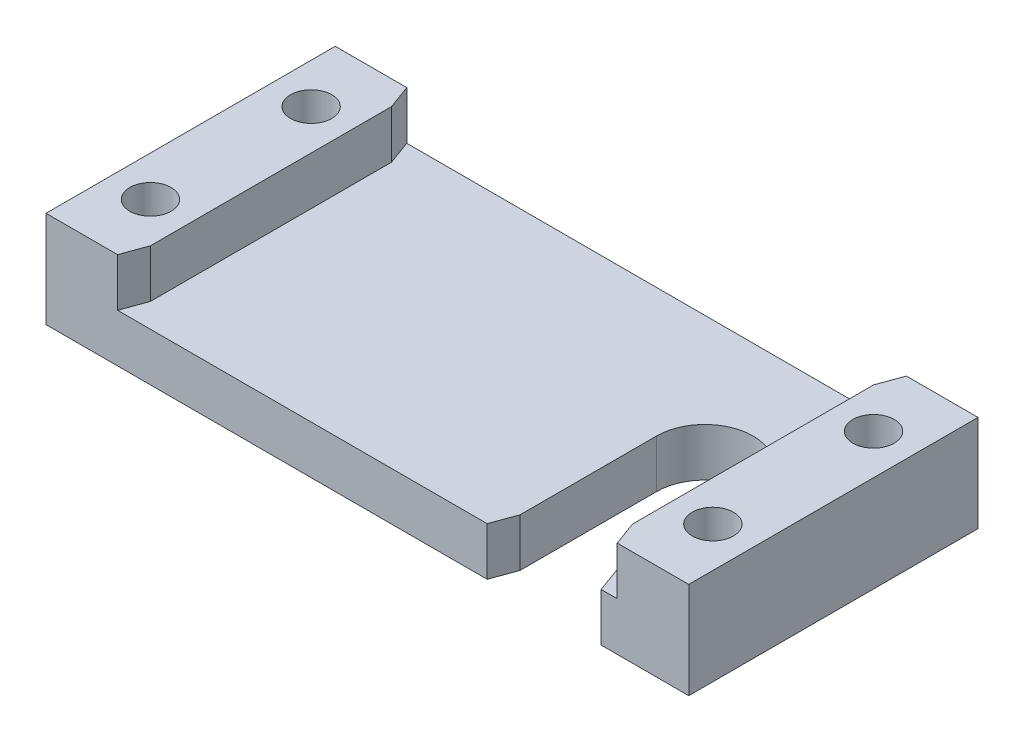
SolidWorks part; units mm, degrees
material "Delrin 2700 NC010, Low Viscosity Acetal Copolymer (SS)"
ref_plane "Front Plane" through (0, 0, 0) normal (0, 0, 1) x (1, 0, 0)
ref_plane "Top Plane" through (0, 0, 0) normal (0, 1, 0) x (1, 0, 0)
ref_plane "Right Plane" through (0, 0, 0) normal (1, 0, 0) x (0, 0, -1)
sketch "Sketch1" plane through (0, 0, 0) normal (0, 0, 1) x (1, 0, 0)
  line L1 (-25.4, 3.81) -> (25.4, 3.81)
  line L2 (-25.4, 3.81) -> (-25.4, -3.81)
  line L3 (-25.4, -3.81) -> (25.4, -3.81)
  line L4 (25.4, 3.81) -> (25.4, -3.81)
  line L5 (-25.4, 3.81) -> (25.4, -3.81) construction
  line L6 (-25.4, -3.81) -> (25.4, 3.81) construction
  line L7 (-19.05, 3.81) -> (19.05, 3.81)
  line L8 (-19.05, 3.81) -> (-19.05, 0)
  line L9 (-19.05, 0) -> (19.05, 0)
  line L10 (19.05, 3.81) -> (19.05, 0)
  point P0 (0, 0)
  point P11 (0, 0)
  dimension "D1" = 50.8
  dimension "D2" = 7.62
  dimension "D3" = 38.1
  dimension "D4" = 3.81
extrude "Boss-Extrude1" add sketch "Sketch1" along normal mid plane 22.86 contours L1 L10 L9 L8 L2 L3 L4
hole_wizard "#4 Clearance Hole1" positions "Sketch2" profile "Sketch3" hole size "#4" standard "ANSI Inch" end condition through all
sketch "Sketch2" plane through (0, 3.81, 0) normal (0, 1, 0) x (1, 0, 0)
  line L1 (-22.225, 6.35) -> (22.225, 6.35)
  line L2 (-22.225, 6.35) -> (-22.225, -6.35)
  line L3 (-22.225, -6.35) -> (22.225, -6.35)
  line L4 (22.225, 6.35) -> (22.225, -6.35)
  line L5 (-22.225, 6.35) -> (22.225, -6.35) construction
  line L6 (-22.225, -6.35) -> (22.225, 6.35) construction
  point P2 (22.225, -6.35)
  point P79 (-22.225, 6.35)
  point P80 (-22.225, -6.35)
  point P81 (22.225, 6.35)
  point P97 (-22.225, 0)
  point P98 (0, -6.35)
  dimension "D1" = 44.45
  dimension "D2" = 12.7
sketch "Sketch3" plane through (22.225, 3.81, 6.35) normal (1, 0, 0) x (0, 0, 1)
  line L0 (0, 0) -> (0, 7.62)
  line L1 (0, 7.62) -> (1.6319, 7.62)
  line L2 (1.6319, 7.62) -> (1.6319, 0)
  line L5 (1.6319, 0) -> (0, 0)
  line L11 (0, -6.35) -> (0, 107.95) construction
  dimension "Thru Hole Dia." = 3.2639
  dimension "Thru Hole Depth" = 7.62
sketch "Sketch4" plane through (0, 0, 0) normal (0, 1, 0) x (1, 0, 0)
  line L0 (17.78, -11.43) -> (17.78, 1.27)
  line L1 (10.16, 1.27) -> (10.16, -11.43)
  line L2 (-19.05, -11.43) -> (19.05, -11.43) construction
  line L5 (17.78, -11.43) -> (10.16, -11.43)
  line L6 (19.05, -11.43) -> (19.05, 11.43) construction
  arc A0 (17.78, 1.27) -> (10.16, 1.27) centre (13.97, 1.27) ccw
  dimension "D1" = 12.7
  dimension "D2" = 1.27
  dimension "D3" = 7.62
extrude "Cut-Extrude1" cut sketch "Sketch4" against normal through all
chamfer "Chamfer1" distance 1.905 angle 20 6 edges at (19.05, 1.905, -11.43) (19.05, 1.905, 11.43) (-19.05, 1.905, -11.43) (-19.05, 1.905, 11.43) (10.16, -1.905, 11.43) (17.78, -1.905, 11.43)
